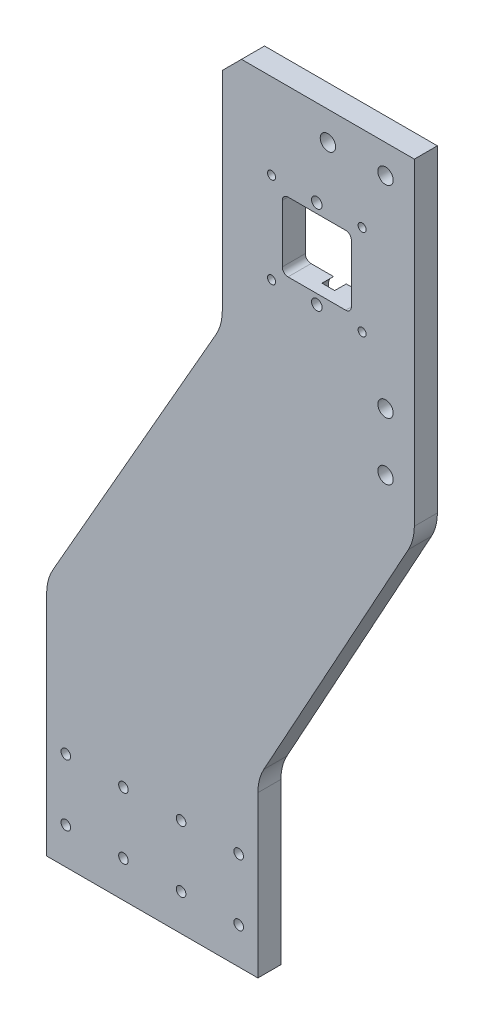
SolidWorks part; units mm, degrees
ref_plane "Plan de face" through (0, 0, 0) normal (0, 0, 1) x (1, 0, 0)
ref_plane "Plan de dessus" through (0, 0, 0) normal (0, 1, 0) x (1, 0, 0)
ref_plane "Plan de droite" through (0, 0, 0) normal (1, 0, 0) x (0, 0, -1)
sketch "Esquisse1" plane through (0, 0, 0) normal (0, 0, 1) x (1, 0, 0)
  line L0 (0, 0) -> (110, 0)
  line L1 (91.4634, 400) -> (91.4634, 291.6413)
  line L2 (101.4634, 410) -> (191.4634, 410)
  line L3 (191.4634, 410) -> (191.4634, 205) construction
  line L4 (0, 0) -> (0, 205) construction
  line L5 (0, 205) -> (191.4634, 205) construction
  line L6 (191.4634, 410) -> (191.4634, 244.4258)
  line L7 (113.0986, 95.6294) -> (188.3648, 232.3706)
  line L8 (88.1675, 279.2343) -> (3.296, 130.7657)
  line L9 (110, 0) -> (110, 83.5742)
  line L10 (0, 118.3587) -> (0, 0)
  line L11 (122.6934, 342) -> (173.0559, 342) construction
  line L12 (155.6934, 360) -> (125.6934, 360)
  line L13 (158.6934, 357) -> (158.6934, 327)
  line L14 (155.6934, 324) -> (125.6934, 324)
  line L15 (122.6934, 357) -> (122.6934, 327)
  line L16 (140.6934, 342) -> (158.6934, 324) construction
  line L17 (140.6934, 324) -> (140.6934, 360) construction
  line L18 (140.6934, 324) -> (140.6934, 314.8947) construction
  line L19 (-30.2925, 35) -> (115.1659, 35) construction
  line L20 (55, 0) -> (55, 66.4475) construction
  line L21 (10, 51) -> (40, 51) construction
  line L22 (40, 51) -> (40, 19) construction
  line L23 (40, 19) -> (10, 19) construction
  line L24 (10, 19) -> (10, 51) construction
  line L25 (101.4634, 410) -> (91.4634, 400)
  arc A0 (191.4634, 244.4258) -> (188.3648, 232.3706) centre (166.4634, 244.4258) cw
  arc A1 (91.4634, 291.6413) -> (88.1675, 279.2343) centre (66.4634, 291.6413) cw
  arc A2 (3.296, 130.7657) -> (0, 118.3587) centre (25, 118.3587) ccw
  arc A3 (113.0986, 95.6294) -> (110, 83.5742) centre (135, 83.5742) ccw
  arc A4 (122.6934, 327) -> (125.6934, 324) centre (125.6934, 327) ccw
  arc A5 (158.6934, 327) -> (155.6934, 324) centre (155.6934, 327) cw
  arc A6 (125.6934, 360) -> (122.6934, 357) centre (125.6934, 357) ccw
  arc A7 (158.6934, 357) -> (155.6934, 360) centre (155.6934, 357) ccw
  circle A10 centre (40, 51) radius 2.5
  circle A11 centre (40, 19) radius 2.5
  circle A12 centre (164.2634, 318.43) radius 2.1
  circle A13 centre (117.1234, 318.43) radius 2.1
  circle A14 centre (164.2634, 365.57) radius 2.1
  circle A15 centre (117.1234, 365.57) radius 2.1
  circle A16 centre (10, 51) radius 2.5
  circle A17 centre (10, 19) radius 2.5
  circle A18 centre (100, 51) radius 2.5
  circle A19 centre (100, 19) radius 2.5
  circle A20 centre (70, 19) radius 2.5
  circle A21 centre (70, 51) radius 2.5
  circle A22 centre (176.4634, 395) radius 4
  circle A23 centre (146.4634, 395) radius 4
  circle A24 centre (176.4634, 290) radius 4
  circle A25 centre (176.4634, 260) radius 4
  circle A26 centre (140.6934, 319) radius 2.75
  circle A27 centre (140.6934, 365) radius 2.75
  point P3 (91.4634, 410)
  point P17 (191.4634, 238)
  point P20 (91.4634, 285)
  point P23 (0, 125)
  point P26 (110, 90)
  point P29 (122.6934, 324)
  point P34 (122.6934, 360)
  point P37 (158.6934, 360)
  dimension "D14" = 25
  dimension "D15" = 25
  dimension "D16" = 25
  dimension "D17" = 25
  dimension "D18" = 3
  dimension "D24" = 47.14
  dimension "D26" = 30
  dimension "D30" = 8
  dimension "D35" = 8
  dimension "D37" = 8
  dimension "D39" = 5.5
  dimension "D40" = 23
  dimension "D1" = 125
  dimension "D2" = 205
  dimension "D3" = 205
  dimension "D4" = 110
  dimension "D5" = 100
  dimension "D6" = 125
  dimension "D7" = 172
  dimension "D8" = 90
  dimension "D9" = 110.1414
  dimension "D10" = 36
  dimension "D11" = 36
  dimension "D12" = 50
  dimension "D13" = 32.77
  dimension "D22" = 115.2874
  dimension "D23" = 110.6152
  dimension "D25" = 47.14
  dimension "D20" = 35
  dimension "D27" = 15
  dimension "D28" = 32
  dimension "D29" = 16
  dimension "D31" = 15
  dimension "D32" = 15
  dimension "D34" = 105
  dimension "D38" = 30
  dimension "D33" = 2
extrude "Boss.-Extru.1" add sketch "Esquisse1" along normal blind 12
sketch "Esquisse2" plane through (0, 0, 0) normal (0, 0, -1) x (-1, 0, 0)
  circle A0 centre (-100, 51) radius 4.5
  circle A1 centre (-70, 51) radius 4.5
  circle A2 centre (-40, 51) radius 4.5
  circle A3 centre (-10, 51) radius 4.5
  circle A4 centre (-70, 19) radius 4.5
  circle A5 centre (-40, 19) radius 4.5
  circle A6 centre (-10, 19) radius 4.5
  circle A7 centre (-100, 19) radius 4.5
  dimension "D1" = 4
  dimension "D3" = 9
  dimension "D2" = 2
extrude "Enlèv. mat.-Extru.1" cut sketch "Esquisse2" against normal blind 5
sketch "Esquisse3" plane through (0, 0, 0) normal (0, 0, -1) x (-1, 0, 0)
  text T0 "<b>GAUCHE</b>"
extrude "Enlèv. mat.-Extru.2" cut sketch "Esquisse3" against normal blind 1
sketch "Esquisse4" plane through (0, 0, 0) normal (0, 0, -1) x (-1, 0, 0)
  circle A0 centre (-140.6934, 365) radius 6
  circle A1 centre (-140.6934, 319) radius 6
  dimension "D1" = 12
  dimension "D2" = 12
extrude "Enlèv. mat.-Extru.5" cut sketch "Esquisse4" against normal blind 6
sketch "Esquisse6" plane through (0, 0, 0) normal (0, -1, 0) x (1, 0, 0)
  line L0 (0, 6) -> (110, 6) construction
  line L1 (0, 12) -> (0, 0) construction
  line L2 (110, 12) -> (110, 0) construction
  circle A0 centre (15, 6) radius 2.5
  circle A1 centre (55, 6) radius 2.5
  circle A2 centre (95, 6) radius 2.5
  dimension "D1" = 5
  dimension "D2" = 5
  dimension "D3" = 5
  dimension "D4" = 15
  dimension "D5" = 15
  dimension "D6" = 55
extrude "Enlèv. mat.-Extru.6" cut sketch "Esquisse6" against normal blind 10
